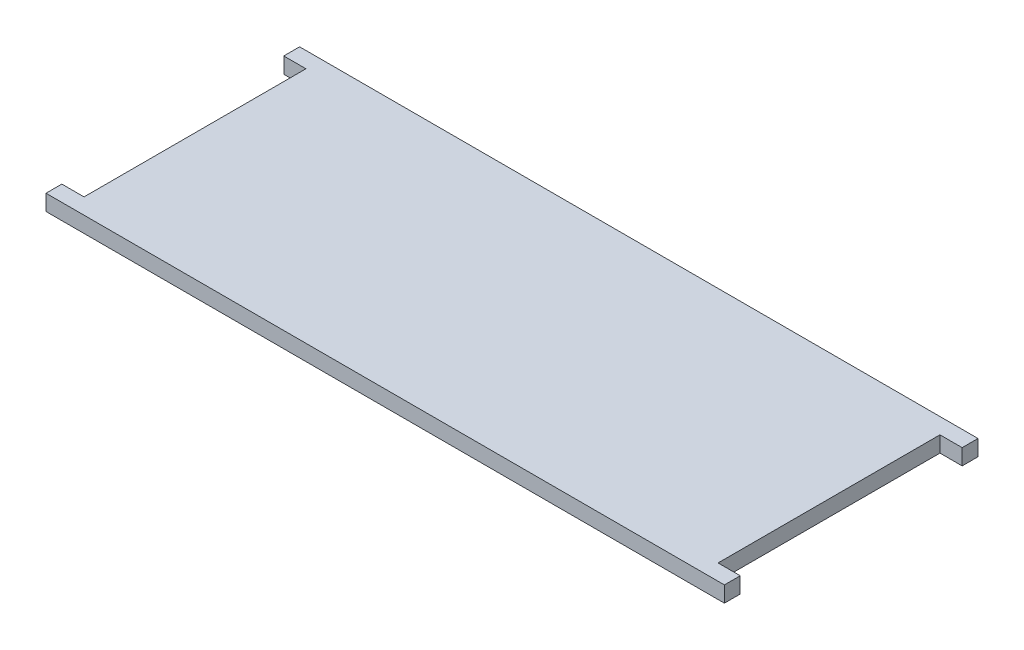
SolidWorks part; units mm, degrees
ref_plane "Front Plane" through (0, 0, 0) normal (0, 0, 1) x (1, 0, 0)
ref_plane "Top Plane" through (0, 0, 0) normal (0, 1, 0) x (1, 0, 0)
ref_plane "Right Plane" through (0, 0, 0) normal (1, 0, 0) x (0, 0, -1)
sketch "Sketch1" plane through (0, 0, 0) normal (0, 1, 0) x (1, 0, 0)
  line L1 (-63.5, 25.4) -> (63.5, 25.4)
  line L2 (-63.5, 25.4) -> (-63.5, -25.4)
  line L3 (-63.5, -25.4) -> (63.5, -25.4)
  line L4 (63.5, 25.4) -> (63.5, -25.4)
  line L5 (-63.5, 25.4) -> (63.5, -25.4) construction
  line L6 (-63.5, -25.4) -> (63.5, 25.4) construction
  line L7 (-63.5, 25.4) -> (-67.945, 25.4)
  line L8 (-63.5, 25.4) -> (-63.5, 22.225)
  line L9 (-63.5, 22.225) -> (-67.945, 22.225)
  line L10 (-67.945, 25.4) -> (-67.945, 22.225)
  line L11 (-63.5, -25.4) -> (-67.945, -25.4)
  line L12 (-63.5, -25.4) -> (-63.5, -22.225)
  line L13 (-63.5, -22.225) -> (-67.945, -22.225)
  line L14 (-67.945, -25.4) -> (-67.945, -22.225)
  line L15 (63.5, 25.4) -> (67.945, 25.4)
  line L16 (63.5, 25.4) -> (63.5, 22.225)
  line L17 (63.5, 22.225) -> (67.945, 22.225)
  line L18 (67.945, 25.4) -> (67.945, 22.225)
  line L19 (63.5, -25.4) -> (67.945, -25.4)
  line L20 (63.5, -25.4) -> (63.5, -22.225)
  line L21 (63.5, -22.225) -> (67.945, -22.225)
  line L22 (67.945, -25.4) -> (67.945, -22.225)
  point P0 (0, 0)
  dimension "D1" = 127
  dimension "D2" = 25.4
  dimension "D3" = 3.175
  dimension "D4" = 4.445
extrude "Boss-Extrude1" add sketch "Sketch1" along normal blind 3.175 contours L4 L1 L2 L3 | L7 L10 L9 L2 | L14 L11 L2 L13 | L19 L22 L21 L4 | L18 L15 L4 L17
